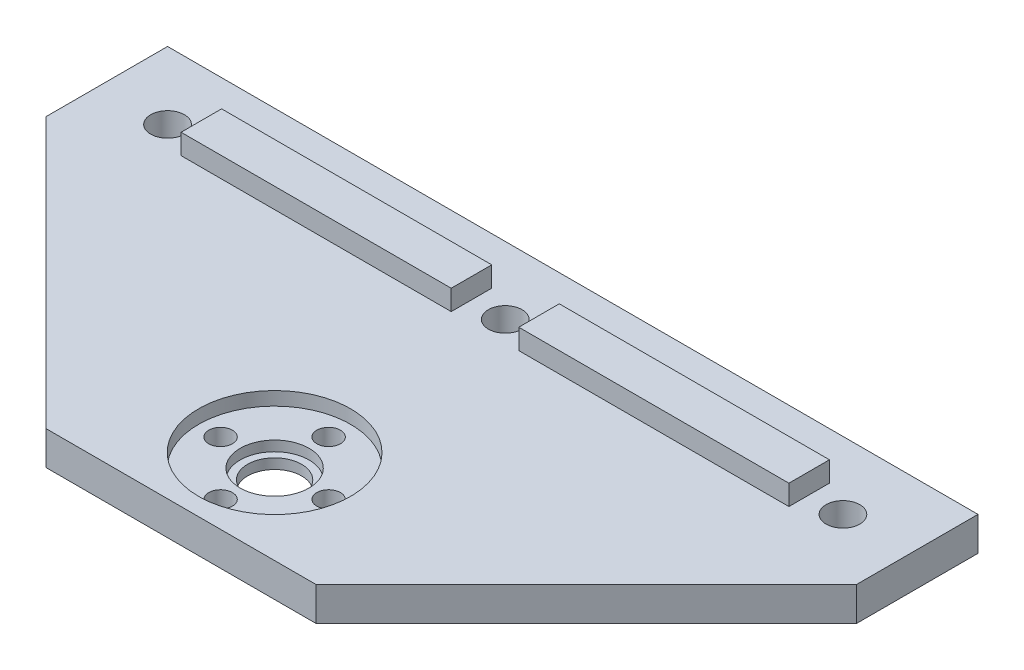
SolidWorks part; units mm, degrees
ref_plane "Front Plane" through (0, 0, 0) normal (0, 0, 1) x (1, 0, 0)
ref_plane "Top Plane" through (0, 0, 0) normal (0, 1, 0) x (1, 0, 0)
ref_plane "Right Plane" through (0, 0, 0) normal (1, 0, 0) x (0, 0, -1)
sketch "Sketch1" plane through (0, 0, 0) normal (0, 1, 0) x (1, 0, 0)
  line L1 (0, 0) -> (120, 0)
  line L2 (0, 0) -> (0, 58)
  line L3 (0, 58) -> (120, 58)
  line L4 (120, 0) -> (120, 58)
  point P6 (0, 0)
  point P7 (0, 0)
  point P8 (0, 0)
  point P9 (0, 0)
  point P10 (0, 0)
  point P11 (0, 0)
  point P12 (0, 0)
  point P13 (0, 0)
  point P14 (0, 0)
  point P15 (0, 0)
  point P16 (0, 0)
  point P17 (0, 0)
  point P18 (99.8191, 0)
  point P19 (0, 0)
  point P20 (0, 0)
  point P21 (0, 0)
  point P22 (0, 0)
  point P23 (0, 0)
extrude "Boss-Extrude5" add sketch "Sketch1" along normal blind 5
sketch "Sketch5" plane through (0, 5, 0) normal (0, 1, 0) x (1, 0, 0)
  circle A0 centre (10, 48) radius 2.5
  circle A1 centre (60, 48) radius 2.5
  circle A2 centre (110, 48) radius 2.5
extrude "Cut-Extrude2" cut sketch "Sketch5" against normal blind 5
sketch "Sketch6" plane through (0, 5, 0) normal (0, 1, 0) x (1, 0, 0)
  line L1 (15, 45) -> (55, 45)
  line L2 (15, 45) -> (15, 51)
  line L3 (15, 51) -> (55, 51)
  line L4 (55, 45) -> (55, 51)
  line L5 (65, 45) -> (105, 45)
  line L6 (65, 45) -> (65, 51)
  line L7 (65, 51) -> (105, 51)
  line L8 (105, 45) -> (105, 51)
  point P8 (0, 0)
  point P9 (0, 0)
  point P10 (0, 0)
  point P11 (0, 0)
  point P12 (0, 0)
  point P13 (0, 0)
  point P14 (0, 0)
extrude "Boss-Extrude6" add sketch "Sketch6" along normal blind 3
sketch "Sketch7" plane through (0, 5, 0) normal (0, 1, 0) x (1, 0, 0)
  circle A6 centre (60, 13.85) radius 11.25
  circle A8 centre (110, 48) radius 2.5 construction
  point P0 (0, 0)
  dimension "D1" = 34.15
extrude "Cut-Extrude3" cut sketch "Sketch7" against normal blind 2
sketch "Sketch8" plane through (0, 3, 0) normal (0, 1, 0) x (1, 0, 0)
  circle A0 centre (60, 13.85) radius 4
extrude "Cut-Extrude4" cut sketch "Sketch8" against normal blind 12
sketch "Sketch9" plane through (0, 3, 0) normal (0, 1, 0) x (1, 0, 0)
  circle A0 centre (60, 13.85) radius 5.1
extrude "Cut-Extrude5" cut sketch "Sketch9" against normal blind 1.5
sketch "Sketch10" plane through (0, 3, 0) normal (0, 1, 0) x (1, 0, 0)
  circle A0 centre (52, 13.85) radius 1.75
  circle A1 centre (60, 21.85) radius 1.75
  circle A2 centre (68, 13.85) radius 1.75
  circle A3 centre (60, 5.85) radius 1.75
extrude "Cut-Extrude6" cut sketch "Sketch10" against normal blind 21.5
chamfer "Chamfer1" distance 40 angle 45 2 edges at (0, 2.5, 0) (120, 2.5, 0)
